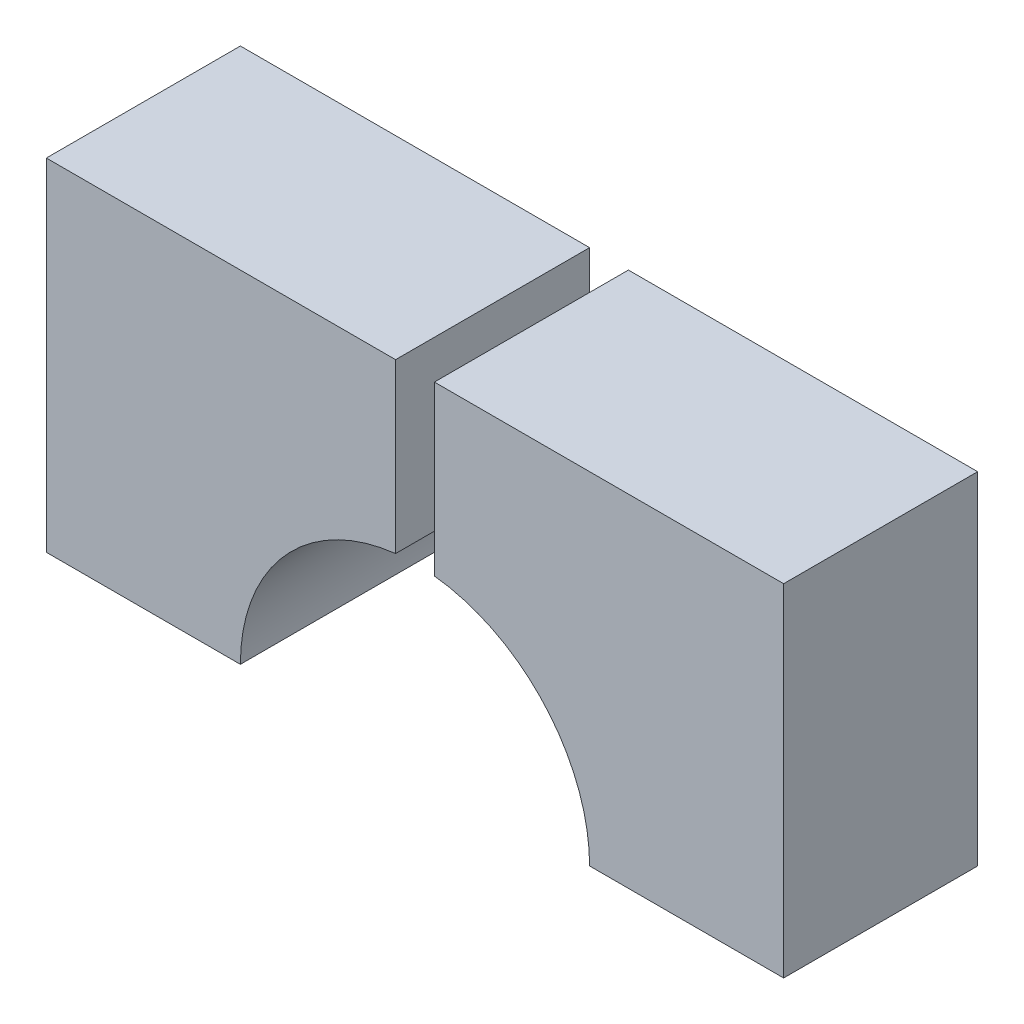
SolidWorks part; units mm, degrees
ref_plane "Front Plane" through (0, 0, 0) normal (0, 0, 1) x (1, 0, 0)
ref_plane "Top Plane" through (0, 0, 0) normal (0, 1, 0) x (1, 0, 0)
ref_plane "Right Plane" through (0, 0, 0) normal (1, 0, 0) x (0, 0, -1)
sketch "Sketch2" plane through (0, 0, 0) normal (0, 0, 1) x (1, 0, 0)
  line L0 (190, -505.6503) -> (-190, -505.6503)
  line L1 (190, -505.6503) -> (190, -329.6503)
  line L2 (0, -505.6503) -> (0, -329.6503)
  line L3 (10, -505.6503) -> (10, -329.6503)
  line L4 (190, -329.6503) -> (0, -329.6503)
  arc A0 (88.6225, -521.3364) -> (-88.6225, -489.9643) centre (0, -505.6503) ccw construction
  arc A1 (88.6225, -521.3364) -> (-88.6225, -489.9643) centre (0, -505.6503) ccw
  circle A2 centre (0, -505.6503) radius 90
  point P4 (90, -505.6503)
  point P8 (0, -505.6503)
  dimension "D1" = 100
  dimension "D2" = 10
extrude "Boss-Extrude1" add sketch "Sketch2" against normal blind 100 from offset 30 offset against normal yes
mirror "Mirror3" about plane through (0, 0, 0) normal (1, 0, 0) of bodies 101
